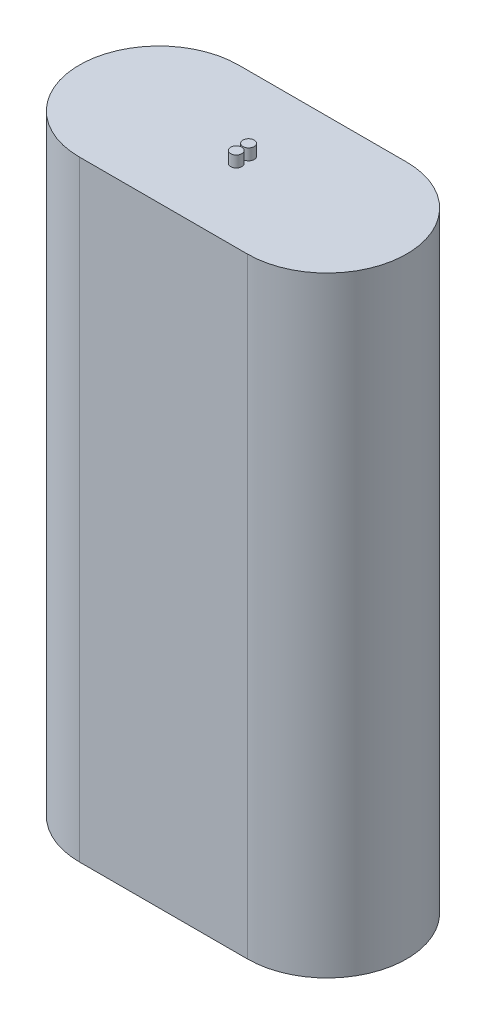
SolidWorks part; units mm, degrees
ref_plane "Front Plane" through (0, 0, 0) normal (0, 0, 1) x (1, 0, 0)
ref_plane "Top Plane" through (0, 0, 0) normal (0, 1, 0) x (1, 0, 0)
ref_plane "Right Plane" through (0, 0, 0) normal (1, 0, 0) x (0, 0, -1)
sketch "Sketch1" plane through (0, 0, 0) normal (0, 1, 0) x (1, 0, 0)
  line L1 (0, 0) -> (19, 0)
  line L2 (0, 0) -> (0, 18)
  line L3 (0, 18) -> (19, 18)
  line L4 (19, 0) -> (19, 18)
  arc A0 (19, 0) -> (19, 18) centre (19, 9) ccw
  arc A1 (0, 18) -> (0, 0) centre (0, 9) ccw
  dimension "D1" = 18
  dimension "D2" = 19
extrude "Boss-Extrude1" add sketch "Sketch1" along normal blind 69 contours L2 A1 | L1 L4 L3 L2 | L4 A0
sketch "Sketch2" plane through (0, 69, 0) normal (0, 1, 0) x (1, 0, 0)
  line L0 (9.5, 18) -> (9.5, 0) construction
  line L1 (0, 18) -> (19, 18) construction
  line L2 (0, 0) -> (19, 0) construction
  line L3 (-9, 9) -> (28, 9) construction
  arc A0 (0, 18) -> (0, 0) centre (0, 9) ccw construction
  arc A1 (19, 0) -> (19, 18) centre (19, 9) ccw construction
  circle A2 centre (9.5, 9.635) radius 0.635
  circle A3 centre (9.5, 8.365) radius 0.635
  dimension "D1" = 1.27
  dimension "D2" = 1.27
extrude "Boss-Extrude2" add sketch "Sketch2" along normal blind 1.27 contours A2
sketch "Sketch3" plane through (0, 69, 0) normal (0, 1, 0) x (1, 0, 0)
  line L0 (-9, 9) -> (28, 9) construction
  line L1 (9.5, 0) -> (9.5, 18) construction
  line L2 (0, 0) -> (19, 0) construction
  line L3 (0, 18) -> (19, 18) construction
  arc A0 (0, 18) -> (0, 0) centre (0, 9) ccw construction
  arc A1 (19, 0) -> (19, 18) centre (19, 9) ccw construction
  circle A2 centre (9.5, 8.238) radius 0.635
  dimension "D1" = 1.27
  dimension "D2" = 0.762
extrude "Boss-Extrude4" add sketch "Sketch3" along normal blind 1.27
